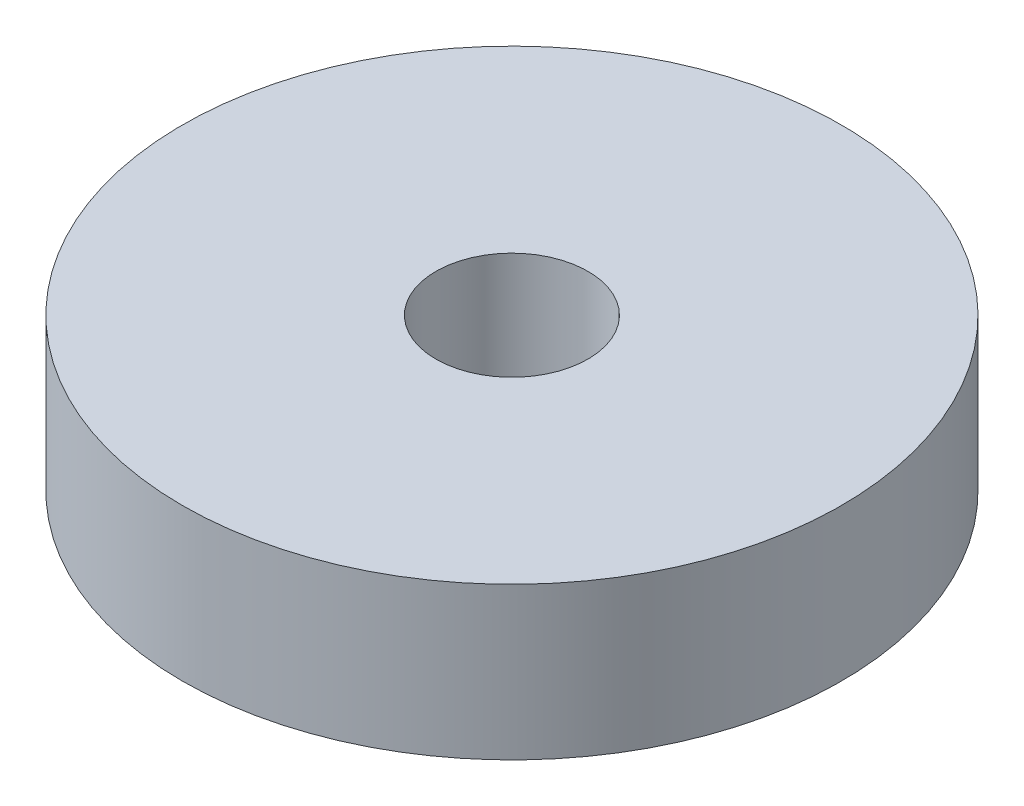
SolidWorks part; units mm, degrees
ref_plane "前基準面" through (0, 0, 0) normal (0, 0, 1) x (1, 0, 0)
ref_plane "上基準面" through (0, 0, 0) normal (0, 1, 0) x (1, 0, 0)
ref_plane "右基準面" through (0, 0, 0) normal (1, 0, 0) x (0, 0, -1)
sketch "草圖1" plane through (0, 0, 0) normal (0, 1, 0) x (1, 0, 0)
  circle A0 centre (0, 0) radius 7.5
  circle A1 centre (0, 0) radius 32.5
  dimension "D1" = 15
  dimension "D2" = 65
extrude "填料-伸長1" add sketch "草圖1" along normal blind 15
